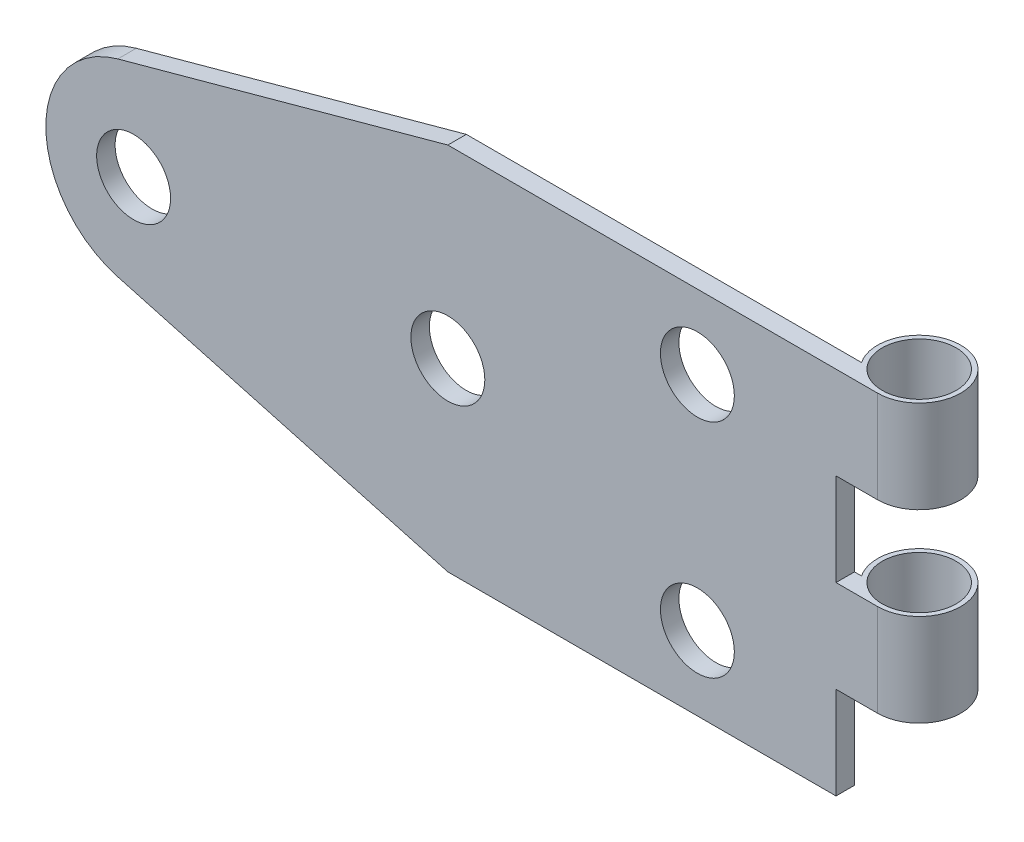
SolidWorks part; units mm, degrees
ref_plane "Front Plane" through (0, 0, 0) normal (0, 0, 1) x (1, 0, 0)
ref_plane "Top Plane" through (0, 0, 0) normal (0, 1, 0) x (1, 0, 0)
ref_plane "Right Plane" through (0, 0, 0) normal (1, 0, 0) x (0, 0, -1)
sketch "Sketch2" plane through (0, 0, 0) normal (0, 0, 1) x (1, 0, 0)
  line L0 (0, 0) -> (0, 20) construction
  line L1 (-4, 0) -> (4, 0) construction
  line L2 (-4, 20) -> (-46.5, 20)
  line L4 (-4, 10) -> (4, 10) construction
  line L5 (4, 10) -> (4, 20) construction
  line L6 (4, 20) -> (-4, 20) construction
  line L7 (-46.5, 20) -> (-82.2111, 10.2113)
  line L8 (0, 0) -> (-90, 0) construction
  line L9 (-46.5, -20) -> (-82.2111, -10.2113)
  line L12 (-4, -10) -> (4, -10) construction
  line L13 (-4, -20) -> (-46.5, -20)
  line L14 (-4, 10) -> (-4, 0)
  line L15 (-4, 0) -> (4, 0) construction
  line L16 (4, -10) -> (4, 0) construction
  line L17 (-4, -10) -> (-4, -20)
  line L18 (-4, 10) -> (-4, 20)
  line L19 (-4, 0) -> (-4, -10)
  arc A1 (-82.2111, 10.2113) -> (-82.2111, -10.2113) centre (-79.4121, 0) ccw
  point P18 (-90, 0)
  dimension "D8" = 10.5879
  dimension "D1" = 20
  dimension "D2" = 4
  dimension "D3" = 8
  dimension "D4" = 90
  dimension "D6" = 46.5
extrude "Boss-Extrude1" add sketch "Sketch2" along normal blind 2 contours L7 A1 L9 L13 L17 L12 L16 L1 L14 L4 L5 L6 L2
sketch "Sketch12" plane through (0, 0, 0) normal (0, 1, 0) x (1, 0, 0)
  line L0 (-4, -2) -> (-4, 0)
  line L1 (-4, 0) -> (-3.7417, 0)
  line L2 (-4, -2) -> (0, -2)
  line L3 (0, 0) -> (0, -2) construction
  line L4 (0, -2) -> (0, 2.5) construction
  circle A1 centre (0, 2.5) radius 4
  circle A2 centre (0, 2.5) radius 4.5
  point P10 (-3.859, 0)
  point P12 (0, 0)
  dimension "D1" = 8
  dimension "D2" = 9
  dimension "D3" = 2.5
extrude "Boss-Extrude12" add sketch "Sketch12" along normal mid plane 40 contours A2 A1 | A2 L1 L0 L2
sketch "Sketch3" plane through (0, 0, 0) normal (0, 0, 1) x (1, 0, 0)
  line L0 (0, 10) -> (4.5, 10)
  line L1 (4.5, -20) -> (4.5, 20) construction
  line L2 (0, 10) -> (-4.5, 10)
  line L3 (-4.5, 10) -> (-4.5, 0)
  line L4 (0, 0) -> (0, 10) construction
  line L5 (0, 20) -> (0, -20) construction
  line L6 (0, 10) -> (0, 20) construction
  line L7 (0, 0) -> (0, -10) construction
  line L8 (0, -10) -> (0, -20) construction
  line L9 (-4.5, 0) -> (4.5, 0)
  line L10 (4.5, 10) -> (4.5, 0)
  line L11 (0, -10) -> (4.5, -10)
  line L12 (4.5, -10) -> (4.5, -20)
  line L13 (4.5, -20) -> (0, -20)
  line L14 (0, -20) -> (-4.5, -20)
  line L15 (0, -20) -> (-46.5, -20) construction
  line L16 (-4.5, -20) -> (-4.5, -10)
  line L17 (-4.5, -10) -> (0, -10)
  circle A0 centre (-19.5, -12) radius 4
  circle A1 centre (-19.5, 12) radius 4
  circle A2 centre (-46.5, 0) radius 4
  circle A3 centre (-80.5, 0) radius 4
  dimension "D1" = 8
  dimension "D2" = 19.5
  dimension "D3" = 24
  dimension "D4" = 19.5
  dimension "D5" = 12
  dimension "D6" = 27
  dimension "D7" = 20
  dimension "D8" = 20
  dimension "D9" = 34
extrude "Cut-Extrude1" cut sketch "Sketch3" along normal through all both and the other way through all
